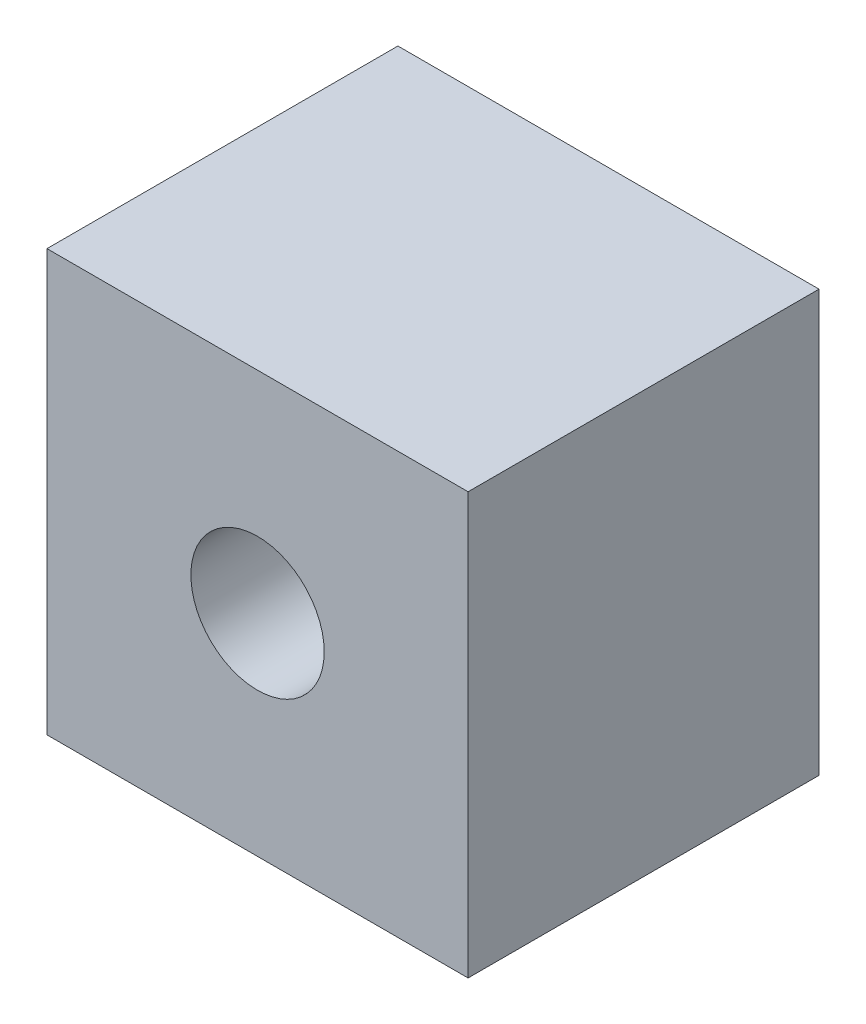
SolidWorks part; units mm, degrees
ref_plane "정면" through (0, 0, 0) normal (0, 0, 1) x (1, 0, 0)
ref_plane "윗면" through (0, 0, 0) normal (0, 1, 0) x (1, 0, 0)
ref_plane "우측면" through (0, 0, 0) normal (1, 0, 0) x (0, 0, -1)
sketch "스케치1" plane through (0, 0, 0) normal (0, 0, 1) x (1, 0, 0)
  line L1 (-6, 6) -> (6, 6)
  line L2 (-6, 6) -> (-6, -6)
  line L3 (-6, -6) -> (6, -6)
  line L4 (6, 6) -> (6, -6)
  line L5 (-6, 6) -> (6, -6) construction
  line L6 (-6, -6) -> (6, 6) construction
  circle A0 centre (0, 0) radius 1.9
  point P0 (0, 0)
  dimension "D2" = 3.8
  dimension "D1" = 12
  dimension "D3" = 12
extrude "보스-돌출1" add sketch "스케치1" along normal blind 10
